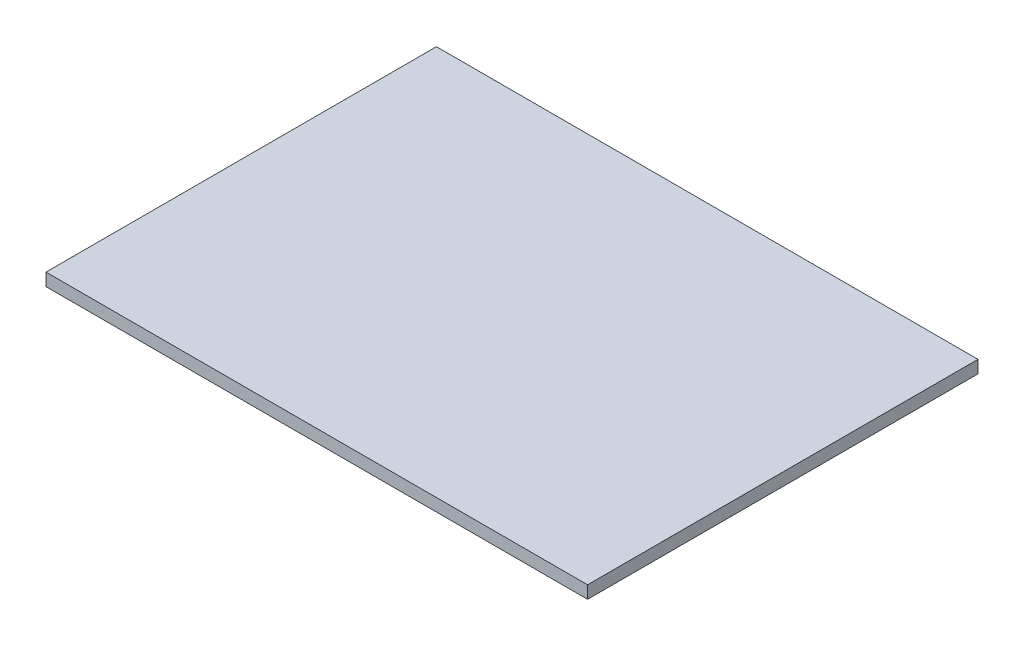
SolidWorks part; units mm, degrees
material "유리"
ref_plane "정면" through (0, 0, 0) normal (0, 0, 1) x (1, 0, 0)
ref_plane "윗면" through (0, 0, 0) normal (0, 1, 0) x (1, 0, 0)
ref_plane "우측면" through (0, 0, 0) normal (1, 0, 0) x (0, 0, -1)
sketch "스케치1" plane through (0, 0, 0) normal (0, 1, 0) x (1, 0, 0)
  line L1 (-107.5, -77.5) -> (107.5, -77.5)
  line L2 (-107.5, -77.5) -> (-107.5, 77.5)
  line L3 (-107.5, 77.5) -> (107.5, 77.5)
  line L4 (107.5, -77.5) -> (107.5, 77.5)
  line L5 (-107.5, -77.5) -> (107.5, 77.5) construction
  line L6 (-107.5, 77.5) -> (107.5, -77.5) construction
  point P0 (0, 0)
  dimension "D1" = 215
  dimension "D2" = 155
extrude "보스-돌출1" add sketch "스케치1" along normal blind 5
